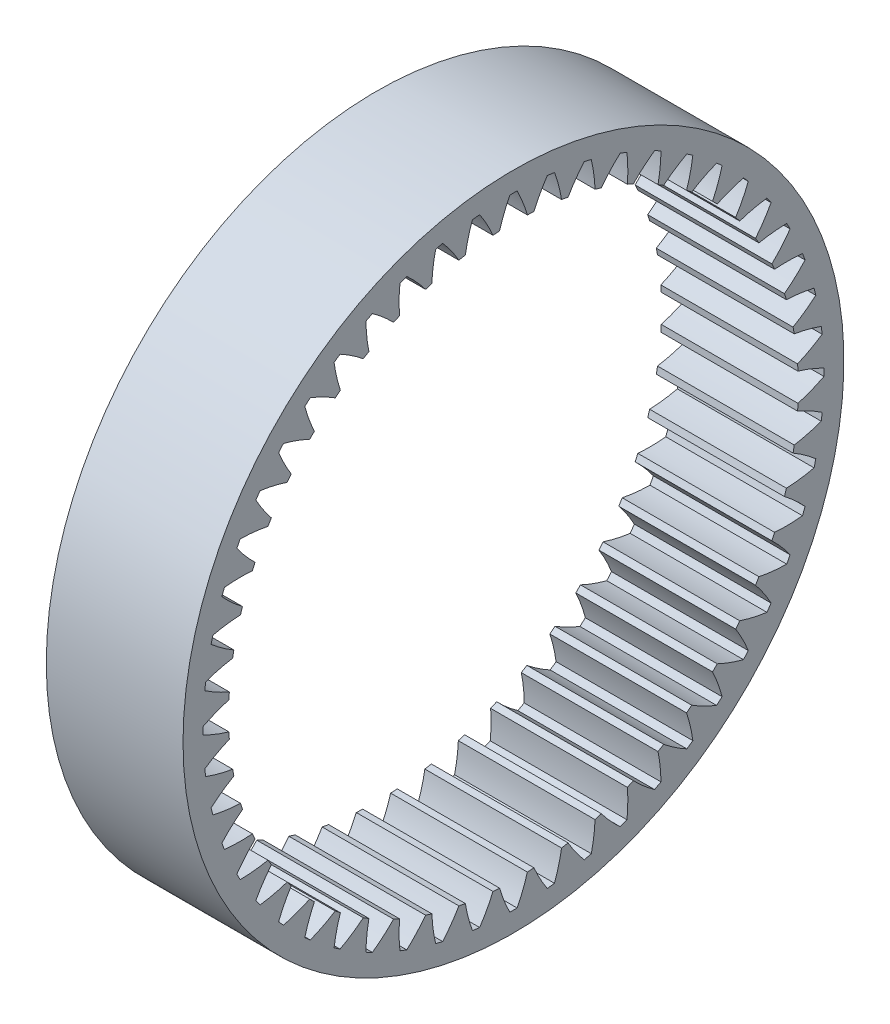
SolidWorks part; units mm, degrees
ref_plane "Plane1" through (0, 0, 0) normal (0, 0, 1) x (1, 0, 0)
ref_plane "Plane2" through (0, 0, 0) normal (0, 1, 0) x (1, 0, 0)
ref_plane "Plane3" through (0, 0, 0) normal (1, 0, 0) x (0, 0, -1)
other "Configuration Table"
sketch "HoldingSke" plane through (0, 0, 0) normal (0, 1, 0) x (1, 0, 0)
  line L0 (0, 0) -> (0.6157, -0.788)
  line L1 (-15, 0) -> (100, 0) construction
  line L2 (0, 0) -> (-2.1039, 2.3779)
  line L3 (0, 0) -> (-11.863, 4.5341)
  line L4 (0, 0) -> (5.3169, 6.8053)
  line L5 (0, 0) -> (-23.7986, -8.8762)
  line L6 (0, 0) -> (-10.5278, -7.1032)
  line L7 (-2.1039, 2.3779) -> (3.3635, 27.1825)
  line L8 (-76.2, 3.3779) -> (-54.61, 3.3779)
  line L9 (-71.009, 38.7566) -> (-53.1078, 45.2721)
  line L10 (-76.2, 71.12) -> (104.1128, 71.12)
  line L11 (0, 0) -> (-12, 0)
  line L12 (-76.2, 101.6) -> (-76.162, 101.6)
  line L13 (24.9733, 27.94) -> (52.9518, 28.4284)
  line L14 (24.9733, 27.94) -> (24.9743, 27.94)
  line L15 (24.9733, 27.94) -> (100.4006, 29.5858)
  circle A0 centre (0, 0) radius 29
  circle A1 centre (0, 0) radius 12.7
  circle A2 centre (0, 0) radius 12.7
  dimension "MHD" = 25.4
  dimension "Hub_dia" = 25.4
  dimension "Diameter" = 58
  dimension "Num_teeth" = 52
  dimension "Pitch" = 1
  dimension "Overall_len" = 25.4
  dimension "Show_teeth" = 52
  dimension "Thickness" = 12.7
  dimension "OAL" = 25.4001
  dimension "T_dim" = 21.59
  dimension "Ap" = 20
  dimension "H" = 19.05
  dimension "Pitch_radius" = 180.3128
  dimension "Width" = 12
  dimension "Backlash" = 0.038
  dimension "Addendum_fac" = 1
  dimension "Dedendum_fac" = 1.25
  dimension "Clearance_fac" = 0.25
  dimension "Dedendum_add" = 0.001
  dimension "Module" = 1
sketch "BasProSke" plane through (0, 0, 0) normal (0, 1, 0) x (1, 0, 0)
  line L0 (-10, 0) -> (60, 0) construction
  line L1 (0, 25) -> (0, 29)
  line L2 (0, 25) -> (12, 25)
  line L3 (12, 25) -> (12, 29)
  line L4 (12, 29) -> (0, 29)
  dimension "Diameter" = 58
  dimension "Thickness" = 12
  dimension "Inside_diameter" = 50
revolve "Base-Revolve" add sketch "BasProSke" angle 360 about L0
sketch "TooCutSke" plane through (0, 0, 0) normal (1, 0, 0) x (0, 0, -1)
  line L3 (0.8803, 25.9851) -> (0.8803, 53.6633) construction
  line L4 (0, 0) -> (0, 59.563) construction
  line L5 (0, 0) -> (-4.1255, 68.2028) construction
  line L6 (-11.2644, 21.3476) -> (36.4461, 24.2336) construction
  circle A0 centre (0, 0) radius 26 construction
  circle A1 centre (0, 0) radius 27.251 construction
  circle A2 centre (0, 0) radius 21.9888 construction
  circle A3 centre (0, 0) radius 24.9746 construction
  arc A4 (1.2281, 24.9444) -> (0.3188, 27.2491) centre (-11.2644, 21.3476) ccw
  arc A5 (1.2281, 24.9444) -> (-1.2281, 24.9444) centre (0, 0) ccw
  arc A6 (0.3188, 27.2491) -> (-0.3188, 27.2491) centre (0, 0) ccw
  arc A7 (-0.3188, 27.2491) -> (-1.2281, 24.9444) centre (11.2644, 21.3476) ccw
  dimension "Pitch_dia" = 52
  dimension "Base_dia" = 43.9776
  dimension "Root_dia" = 54.502
  dimension "Overcut_dia" = 49.9492
  dimension "Flank_rad" = 13
  dimension "Half_ang" = 3.462
  dimension "Half_CT" = 0.8803
extrude "ToothCut" cut sketch "TooCutSke" along normal through all
fillet "Breaks" [suppressed] radius 0.1
fillet "RootFillets" [suppressed] radius 0.251
pattern_circular "TeethCuts" count 52 over 360 about axis through (0, 0, 0) along (1, 0, 0) of "RootFillets", "Breaks", "ToothCut"
equation "' \"Module@HoldingSke\" = 6.35"
equation "' \"Num_teeth@HoldingSke\" = 24"
equation "' \"Ap@HoldingSke\" =  14.5"
equation "' \"Ap@HoldingSke\" = 14.5"
equation "' \"Width@HoldingSke\" = 12"
equation "' \"Diameter@HoldingSke\" = 8 * 25.4"
equation "' \"Show_teeth@HoldingSke\" = 100"
equation "' \"Backlash@HoldingSke\" = 0.009 * 25.4"
equation "' \"Addendum_fac@HoldingSke\" = 1.0"
equation "' \"Dedendum_fac@HoldingSke\" = 1.25"
equation "' \"Dedendum_add@HoldingSke\" = 0.00005 * 25.4"
equation "' \"Clearance_fac@HoldingSke\" = 0.25"
equation "\"Pitch@HoldingSke\" = 1 / \"Module@HoldingSke\" "
equation "\"Overcut_dia@TooCutSke\" = (\"Num_teeth@HoldingSke\" - 2 * \"Addendum_fac@HoldingSke\") / \"Pitch@HoldingSke\" - 0.002 * 25.4"
equation "\"Pitch_dia@TooCutSke\" = \"Num_teeth@HoldingSke\" / \"Pitch@HoldingSke\""
equation "\"Base_dia@TooCutSke\" = \"Num_teeth@HoldingSke\" / \"Pitch@HoldingSke\" * cos((\"Ap@HoldingSke\"  * 3.14159265 / 180)) * 0.90"
equation "\"Root_dia@TooCutSke\" = \"Num_teeth@HoldingSke\"  / \"Pitch@HoldingSke\" + 2 *  \"Dedendum_fac@HoldingSke\"/ \"Pitch@HoldingSke\" + \"Dedendum_add@HoldingSke\" * 2"
equation "\"Half_ang@TooCutSke\" = 180 / \"Num_teeth@HoldingSke\""
equation "\"Half_CT@TooCutSke\" = \"Num_teeth@HoldingSke\" / \"Pitch@HoldingSke\" * sin((3.14159265 / 2 / \"Num_teeth@HoldingSke\")) / 2 + 10 * \"Backlash@HoldingSke\" / 4"
equation "\"Flank_rad@TooCutSke\" = \"Num_teeth@HoldingSke\" / \"Pitch@HoldingSke\" / 4"
equation "\"Radius@RootFillets\"= \"Clearance_fac@HoldingSke\" / \"Pitch@HoldingSke\" + \"Dedendum_add@HoldingSke\""
equation "\"Break_rad@Breaks\" = 0.02 / \"Pitch@HoldingSke\" * 5"
equation "\"Num_teeth@TeethCuts\" = int( \"Show_teeth@HoldingSke\" ) + 1"
equation "\"Num_teeth@TeethCuts\" = ((sgn( \"Num_teeth@TeethCuts\" - \"Num_teeth@HoldingSke\" )-1)*( \"Num_teeth@TeethCuts\" - \"Num_teeth@HoldingSke\" ))/-2+ \"Num_teeth@HoldingSke\""
equation "\"Num_teeth@TeethCuts\" = ((sgn( \"Num_teeth@TeethCuts\" - 2.0)+1)*( \"Num_teeth@TeethCuts\" - 2.0))/2 +2.0"
equation "\"Angle@TeethCuts\" = 360.0 / \"Num_teeth@HoldingSke\""
equation "\"Diameter@BasProSke\" = \"Num_teeth@HoldingSke\"  / \"Pitch@HoldingSke\" + 2 *  \"Dedendum_fac@HoldingSke\"/ \"Pitch@HoldingSke\" + \"Dedendum_add@HoldingSke\" * 2 + 0.002 * 25.4"
equation "\"Diameter@BasProSke\" = ((sgn( \"Diameter@BasProSke\"  - \"Diameter@HoldingSke\" )+1)*( \"Diameter@BasProSke\"  - \"Diameter@HoldingSke\" ))/2 + \"Diameter@HoldingSke\""
equation "\"Inside_diameter@BasProSke\" =  (\"Num_teeth@HoldingSke\" - 2 * \"Addendum_fac@HoldingSke\") / \"Pitch@HoldingSke\" "
equation "\"Thickness@BasProSke\"  = \"Width@HoldingSke\""
